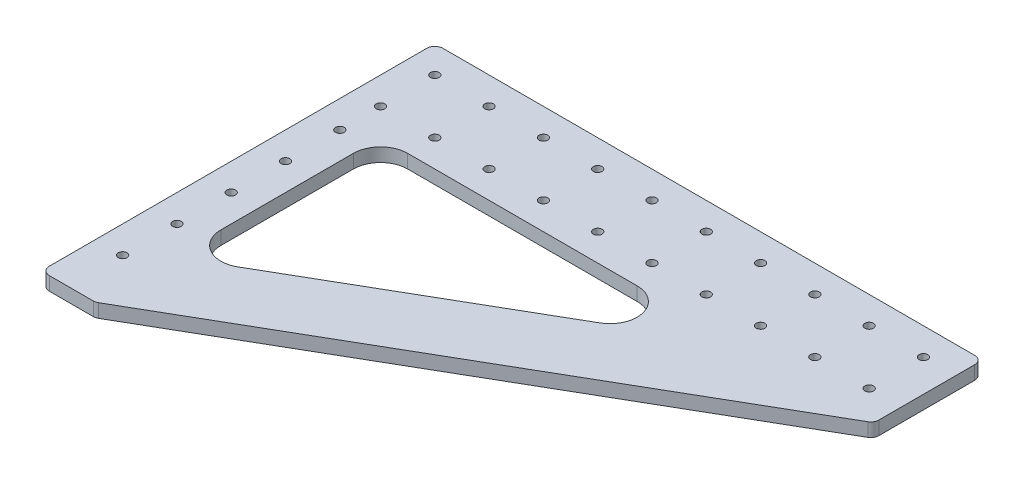
SolidWorks part; units mm, degrees
material "Thornel Mat VMA"
ref_plane "前视基准面" through (0, 0, 0) normal (0, 0, 1) x (1, 0, 0)
ref_plane "上视基准面" through (0, 0, 0) normal (0, 1, 0) x (1, 0, 0)
ref_plane "右视基准面" through (0, 0, 0) normal (1, 0, 0) x (0, 0, -1)
other "Configuration Table"
sketch "草图1" plane through (0, 0, 0) normal (0, 1, 0) x (1, 0, 0)
  line L0 (0, 0) -> (0, -105) construction
  line L1 (0, -105) -> (-20, -105)
  line L2 (-20, -105) -> (-20, 40)
  line L3 (-20, 40) -> (181.8653, 40)
  line L4 (181.8653, 40) -> (181.8653, 0)
  line L5 (181.8653, 0) -> (0, 0) construction
  line L6 (0, -105) -> (181.8653, 0)
  line L7 (0, -76.1325) -> (0, 0)
  line L8 (0, 0) -> (131.8653, 0)
  line L9 (131.8653, 0) -> (0, -76.1325)
  circle A0 centre (-10, -5) radius 1.6
  circle A1 centre (-10, -25) radius 1.6
  circle A2 centre (-10, -45) radius 1.6
  circle A3 centre (-10, 10) radius 1.6
  circle A4 centre (-10, 30) radius 1.6
  circle A5 centre (10, 30) radius 1.6
  circle A6 centre (10, 10) radius 1.6
  circle A7 centre (30, 30) radius 1.6
  circle A8 centre (30, 10) radius 1.6
  circle A9 centre (-10, -65) radius 1.6
  circle A10 centre (-10, -85) radius 1.6
  circle A11 centre (50, 10) radius 1.6
  circle A12 centre (70, 10) radius 1.6
  circle A13 centre (90, 10) radius 1.6
  circle A14 centre (110, 10) radius 1.6
  circle A15 centre (130, 10) radius 1.6
  circle A16 centre (150, 10) radius 1.6
  circle A17 centre (170, 10) radius 1.6
  circle A18 centre (50, 30) radius 1.6
  circle A19 centre (70, 30) radius 1.6
  circle A20 centre (90, 30) radius 1.6
  circle A21 centre (110, 30) radius 1.6
  circle A22 centre (130, 30) radius 1.6
  circle A23 centre (150, 30) radius 1.6
  circle A24 centre (170, 30) radius 1.6
  circle A25 centre (30, 30) radius 1.6
  dimension "D8" = 3.2
  dimension "D17" = 3.2
  dimension "D20" = 3.2
  dimension "D1" = 40
  dimension "D2" = 20
  dimension "D3" = 30
  dimension "D4" = 105
  dimension "D5" = 25
  dimension "D6" = 10
  dimension "D7" = 5
  dimension "D10" = 20
  dimension "D11" = 10
  dimension "D12" = 10
  dimension "D13" = 10
  dimension "D15" = 20
  dimension "D16" = 20
  dimension "D18" = 10
  dimension "D19" = 10
  dimension "D21" = 20
  dimension "D9" = 3
  dimension "D14" = 3
  dimension "D22" = 8
  dimension "D23" = 2
extrude "凸台-拉伸1" add sketch "草图1" along normal blind 5 contours L1 L6 L4 L3 L2 A24 A23 A22 A21 A20 A19 A18 A17 A16 A15 A14 A13 A12 A11 A10 A9 A8 A7 A6 A5 A4 A3 A2
fillet "圆角1" radius 10 3 edges at (0, 2.5, 0) (131.8653, 2.5, 0) (0, 2.5, 76.1325)
fillet "圆角2" radius 3 5 edges at (-20, 2.5, -40) (181.8653, 2.5, -40) (181.8653, 2.5, 0) (0, 2.5, 105) (-20, 2.5, 105)
ref_plane "基准面1" through (-20, 0, 0) normal (1, 0, 0) x (0, 0, -1)
